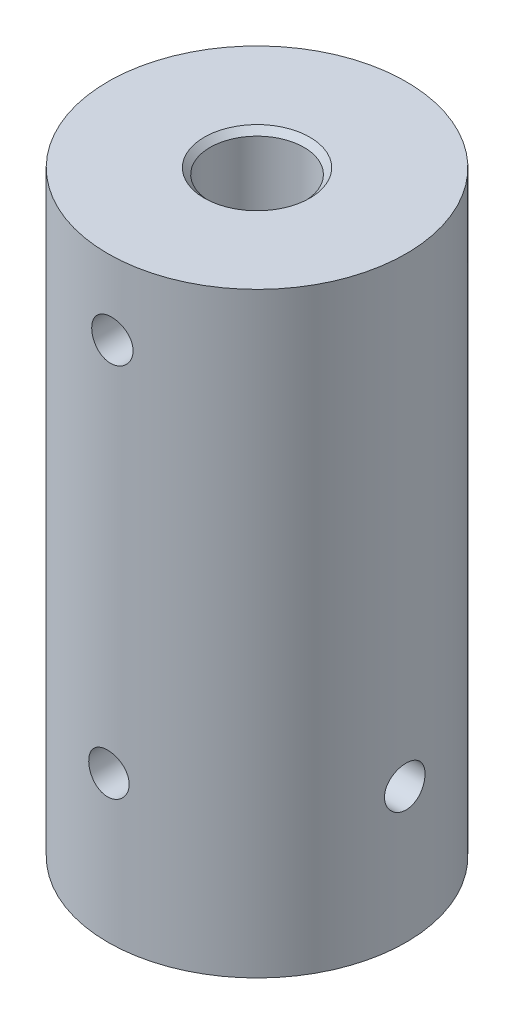
SolidWorks part; units mm, degrees
ref_plane "Front Plane" through (0, 0, 0) normal (0, 0, 1) x (1, 0, 0)
ref_plane "Top Plane" through (0, 0, 0) normal (0, 1, 0) x (1, 0, 0)
ref_plane "Right Plane" through (0, 0, 0) normal (1, 0, 0) x (0, 0, -1)
sketch "Sketch1" plane through (0, 0, 0) normal (0, 1, 0) x (1, 0, 0)
  circle A0 centre (0, 0) radius 12.7
  dimension "D1" = 25.4
extrude "Boss-Extrude1" add sketch "Sketch1" along normal blind 50.8 contours A0
hole_wizard "Ø8.0 (8) Diameter Hole1" positions "Sketch2" profile "Sketch4" hole size "Ø8.0" standard "ANSI Metric"
sketch "Sketch2" plane through (0, 50.8, 0) normal (0, 1, 0) x (1, 0, 0)
  point P0 (0, 0)
sketch "Sketch4" plane through (0, 50.8, 0) normal (1, 0, 0) x (0, 0, 1)
  line L0 (0, 0) -> (0, 18.9134)
  line L1 (0, 18.9134) -> (4, 16.51)
  line L2 (4, 16.51) -> (4, 0.5)
  line L3 (4, 0.5) -> (4.5, 0)
  line L5 (4.5, 0) -> (0, 0)
  line L6 (-4, 0.5) -> (-4.5, 0) construction
  line L10 (0, 18.9134) -> (-4, 16.51) construction
  line L11 (0, -6.35) -> (0, 107.95) construction
  dimension "Hole Dia." = 8
  dimension "Hole Depth" = 16.51
  dimension "Near C'Sink Dia." = 9
  dimension "Near C'Sink Angle" = 90
  dimension "Drill Angle" = 118
hole_wizard "#8-32 Tapped Hole1" positions "3DSketch1" profile "Sketch6" tap size "#8-32" standard "ANSI Inch"
sketch3d "3DSketch1"
  point P0 (0.2589, 44.5517, 12.6974)
sketch "Sketch6" plane through (0.2589, 44.5517, 12.6974) normal (0, 1, 0) x (0.9998, 0, -0.0204)
  line L0 (0, 0) -> (0, 8.7)
  line L1 (0, 8.7) -> (1.7272, 8.7)
  line L2 (1.7272, 8.7) -> (1.7272, 0)
  line L5 (1.7272, 0) -> (0, 0)
  line L11 (0, -6.35) -> (0, 107.95) construction
  dimension "Thru Tap Drill Dia." = 3.4544
  dimension "Thru Tap Drill Depth" = 8.7
cosmetic thread "Hole Thread1" parameters "D2"=4.1656
hole_wizard "3/4 (0.75) Diameter Hole1" positions "Sketch7" profile "Sketch9" hole size "3/4" standard "ANSI Inch"
sketch "Sketch7" plane through (0, 0, 0) normal (0, -1, 0) x (-1, 0, 0)
  point P0 (0, 0)
sketch "Sketch9" plane through (0, 0, 0) normal (1, 0, 0) x (0, 0, -1)
  line L0 (0, 0) -> (0, 28.5832)
  line L1 (0, 28.5832) -> (9.525, 22.86)
  line L2 (9.525, 22.86) -> (9.525, 0.635)
  line L3 (9.525, 0.635) -> (10.16, 0)
  line L5 (10.16, 0) -> (0, 0)
  line L6 (-9.525, 0.635) -> (-10.16, 0) construction
  line L10 (0, 28.5832) -> (-9.525, 22.86) construction
  line L11 (0, -6.35) -> (0, 107.95) construction
  dimension "Hole Dia." = 19.05
  dimension "Hole Depth" = 22.86
  dimension "Near C'Sink Dia." = 20.32
  dimension "Near C'Sink Angle" = 90
  dimension "Drill Angle" = 118
hole_wizard "Tap Drill for #8-32 Tap1" positions "3DSketch2" profile "Sketch11" hole size "#8-32" standard "ANSI Inch"
sketch3d "3DSketch2"
  point P0 (-0.0351, 12.4445, 12.7)
sketch "Sketch11" plane through (-0.0351, 12.4445, 12.7) normal (0, 1, 0) x (1, 0, 0.0028)
  line L0 (0, 0) -> (0, 3.175)
  line L1 (0, 3.175) -> (1.7272, 3.175)
  line L2 (1.7272, 3.175) -> (1.7272, 0)
  line L5 (1.7272, 0) -> (0, 0)
  line L11 (0, -6.35) -> (0, 107.95) construction
  dimension "Thru Hole Dia." = 3.4544
  dimension "Thru Hole Depth" = 3.175
hole_wizard "Tap Drill for #8-32 Tap2" positions "3DSketch3" profile "Sketch12" hole size "#8-32" standard "ANSI Inch"
sketch3d "3DSketch3"
  point P0 (12.7, 11.4994, 0)
sketch "Sketch12" plane through (12.7, 11.4994, 0) normal (0, 1, 0) x (0, 0, -1)
  line L0 (0, 0) -> (0, 3.175)
  line L1 (0, 3.175) -> (1.7272, 3.175)
  line L2 (1.7272, 3.175) -> (1.7272, 0)
  line L5 (1.7272, 0) -> (0, 0)
  line L11 (0, -6.35) -> (0, 107.95) construction
  dimension "Thru Hole Dia." = 3.4544
  dimension "Thru Hole Depth" = 3.175
